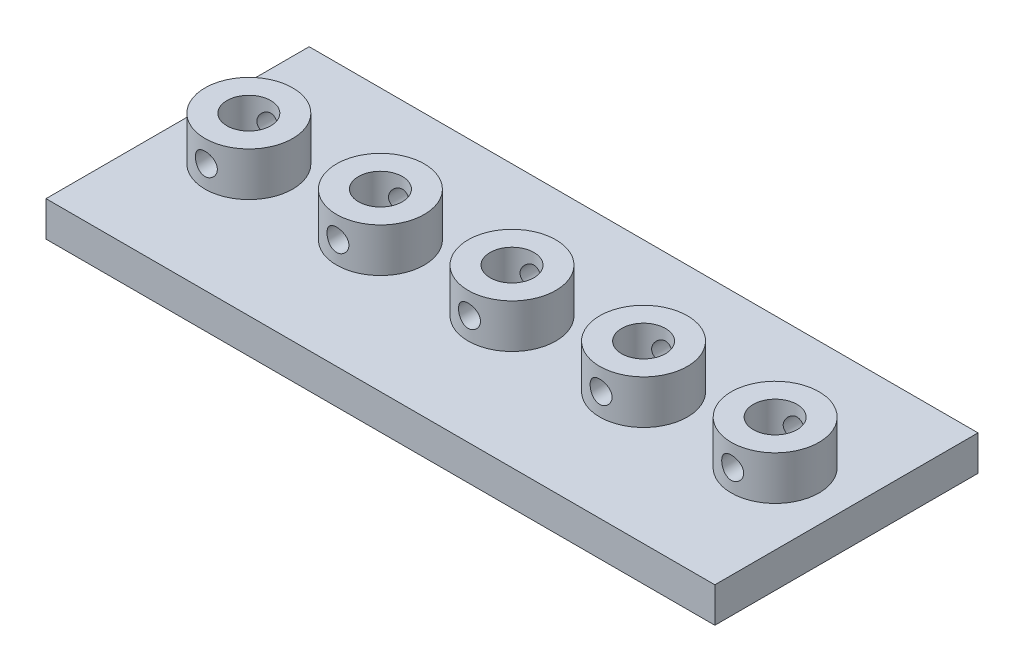
SolidWorks part; units mm, degrees
ref_plane "Front Plane" through (0, 0, 0) normal (0, 0, 1) x (1, 0, 0)
ref_plane "Top Plane" through (0, 0, 0) normal (0, 1, 0) x (1, 0, 0)
ref_plane "Right Plane" through (0, 0, 0) normal (1, 0, 0) x (0, 0, -1)
sketch "Sketch1" plane through (0, 0, 0) normal (0, 1, 0) x (1, 0, 0)
  line L1 (-15.25, 6) -> (15.25, 6)
  line L2 (-15.25, 6) -> (-15.25, -6)
  line L3 (-15.25, -6) -> (15.25, -6)
  line L4 (15.25, 6) -> (15.25, -6)
  line L5 (-15.25, 6) -> (15.25, -6) construction
  line L6 (-15.25, -6) -> (15.25, 6) construction
  point P0 (0, 0)
  dimension "D1" = 12
  dimension "D2" = 30.5
extrude "Boss-Extrude1" add sketch "Sketch1" along normal blind 1.6
sketch "Sketch2" plane through (0, 1.6, 0) normal (0, 1, 0) x (1, 0, 0)
  line L0 (0, 0) -> (6, 0) construction
  line L1 (0, 0) -> (-6, 0) construction
  line L2 (-12, 0) -> (-6, 0) construction
  circle A0 centre (0, 0) radius 2
  circle A1 centre (6, 0) radius 2
  circle A2 centre (12, 0) radius 2
  circle A3 centre (-6, 0) radius 2
  circle A4 centre (-12, 0) radius 2
  circle A5 centre (-12, 0) radius 1
  circle A6 centre (-6, 0) radius 1
  circle A7 centre (0, 0) radius 1
  circle A8 centre (6, 0) radius 1
  circle A9 centre (12, 0) radius 1
  dimension "D1" = 4
  dimension "D6" = 2
  dimension "D3" = 6
  dimension "D5" = 6
  dimension "D8" = 6
  dimension "D2" = 3
  dimension "D4" = 3
  dimension "D7" = 5
extrude "Boss-Extrude2" add sketch "Sketch2" along normal blind 2
sketch "Sketch3" plane through (0, 0, 0) normal (0, 0, 1) x (1, 0, 0)
  line L0 (-12, 3.6) -> (-12, 2.6) construction
  line L1 (-10, 3.6) -> (-14, 3.6) construction
  circle A0 centre (-12, 2.6) radius 0.5
  circle A1 centre (-6, 2.6) radius 0.5
  circle A2 centre (0, 2.6) radius 0.5
  circle A3 centre (6, 2.6) radius 0.5
  circle A4 centre (12, 2.6) radius 0.5
  dimension "D2" = 1
  dimension "D1" = 1
extrude "Cut-Extrude1" cut sketch "Sketch3" against normal blind 2 and the other way blind 2
